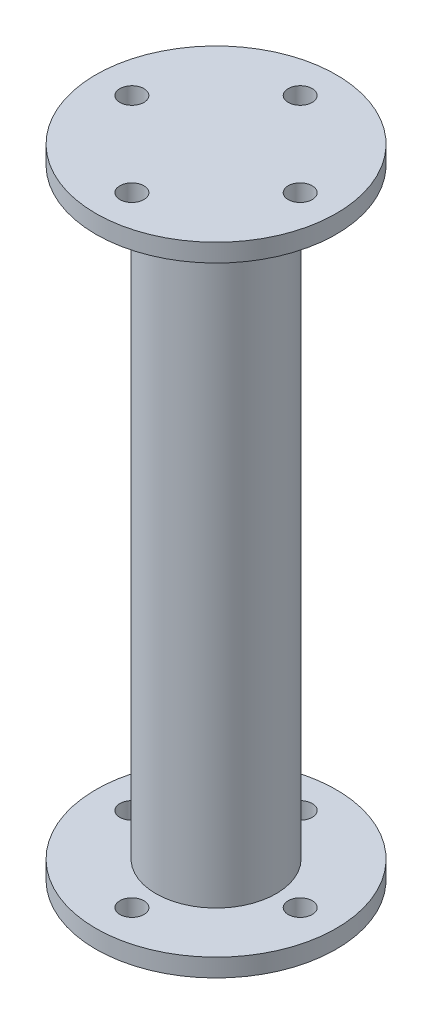
SolidWorks part; units mm, degrees
ref_plane "Front Plane" through (0, 0, 0) normal (0, 0, 1) x (1, 0, 0)
ref_plane "Top Plane" through (0, 0, 0) normal (0, 1, 0) x (1, 0, 0)
ref_plane "Right Plane" through (0, 0, 0) normal (1, 0, 0) x (0, 0, -1)
sketch "Sketch1" plane through (0, 0, 0) normal (0, 1, 0) x (1, 0, 0)
  circle A0 centre (0, 0) radius 10
  circle A1 centre (-7, 0) radius 1
  circle A2 centre (0, 7) radius 1
  circle A3 centre (7, 0) radius 1
  circle A4 centre (0, -7) radius 1
  circle A5 centre (0, 0) radius 2
  dimension "D1" = 4
  dimension "D2" = 2
  dimension "D7" = 20
  dimension "D3" = 7
  dimension "D4" = 7
  dimension "D5" = 7
  dimension "D6" = 7
extrude "Boss-Extrude1" add sketch "Sketch1" along normal blind 1.5 contours A5 | A0 A5 A4 A3 A2 A1
sketch "Sketch2" plane through (0, 1.5, 0) normal (0, 1, 0) x (1, 0, 0)
  circle A0 centre (0, 0) radius 5
  dimension "D1" = 10
extrude "Boss-Extrude2" add sketch "Sketch2" along normal blind 50
ref_plane "Plane1" through (0, 26.5, 0) normal (0, 1, 0) x (1, 0, 0)
mirror "Mirror1" about plane through (0, 26.5, 0) normal (0, 1, 0) of "Boss-Extrude1"
